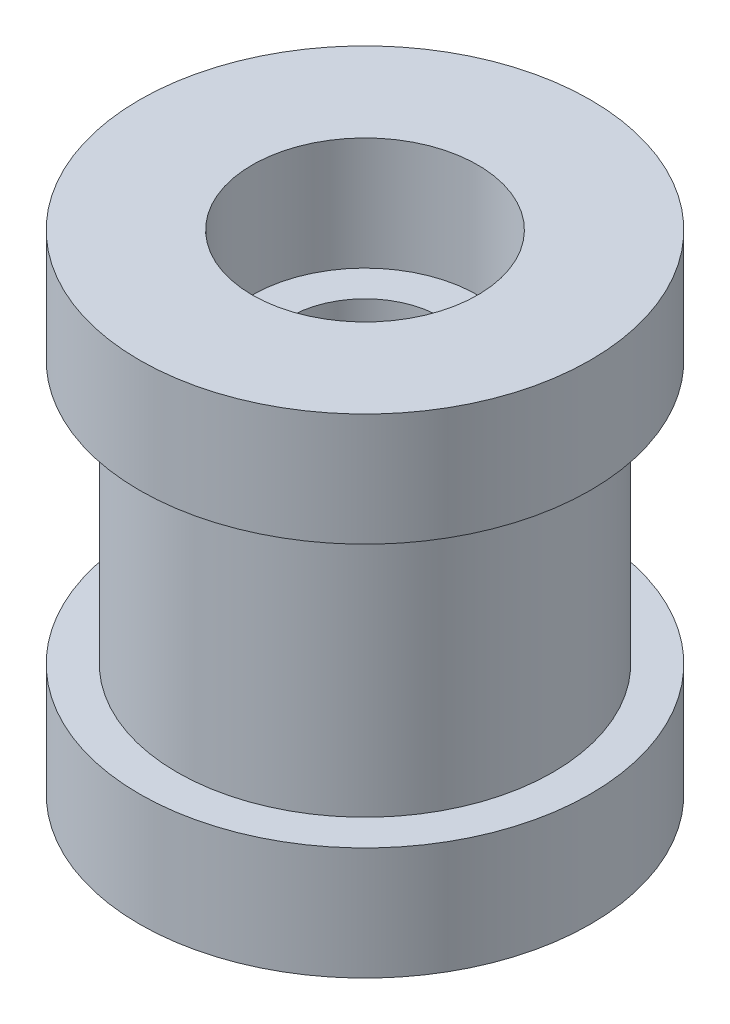
SolidWorks part; units mm, degrees
ref_plane "Alzado" through (0, 0, 0) normal (0, 0, 1) x (1, 0, 0)
ref_plane "Planta" through (0, 0, 0) normal (0, 1, 0) x (1, 0, 0)
ref_plane "Vista lateral" through (0, 0, 0) normal (1, 0, 0) x (0, 0, -1)
sketch "Croquis1" plane through (0, 0, 0) normal (0, 0, 1) x (1, 0, 0)
  line L0 (-45, 36.4841) -> (-30, 36.4841)
  line L1 (-30, 36.4841) -> (-30, 6.4841)
  line L2 (-30, 6.4841) -> (-20, 6.4841)
  line L3 (-20, 6.4841) -> (-20, -8.5159)
  line L4 (-20, -8.5159) -> (-27.5, -8.5159)
  line L5 (-27.5, -8.5159) -> (-35, -8.5159)
  line L6 (-35, -8.5159) -> (-35, -48.5159)
  line L7 (-35, -48.5159) -> (-20, -48.5159)
  line L8 (-20, -48.5159) -> (-20, -63.5159)
  line L9 (-20, -63.5159) -> (-30, -63.5159)
  line L10 (-30, -63.5159) -> (-30, -93.5159)
  line L11 (-30, -93.5159) -> (-60, -93.5159)
  line L12 (-60, -93.5159) -> (-60, -63.5159)
  line L13 (-60, -63.5159) -> (-50, -63.5159)
  line L14 (-50, -63.5159) -> (-50, 6.4841)
  line L15 (-50, 6.4841) -> (-60, 6.4841)
  line L16 (-60, 6.4841) -> (-60, 36.4841)
  line L17 (-60, 36.4841) -> (-45, 36.4841)
  line L18 (0, 96.4584) -> (0, -133.1902) construction
  dimension "D1" = 30
  dimension "D2" = 30
  dimension "D3" = 70
  dimension "D4" = 30
  dimension "D5" = 10
  dimension "D6" = 10
  dimension "D7" = 15
  dimension "D8" = 30
  dimension "D9" = 15
  dimension "D10" = 10
  dimension "D11" = 15
  dimension "D12" = 40
  dimension "D13" = 30
  dimension "D14" = 30
  dimension "D15" = 20
revolve "Revolución2" add sketch "Croquis1" angle 360 about L18
